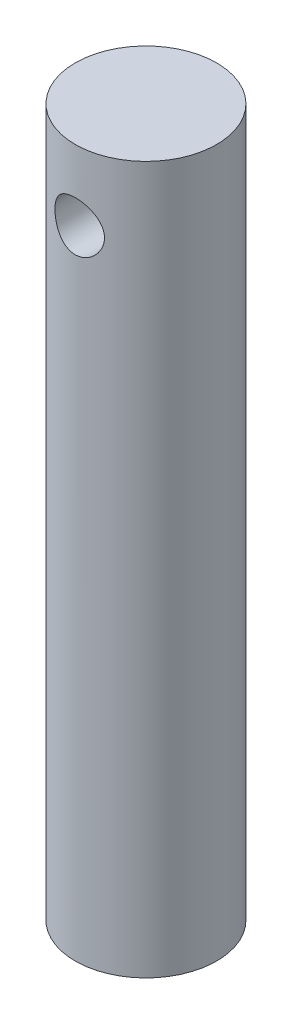
SolidWorks part; units mm, degrees
ref_plane "Plan de face" through (0, 0, 0) normal (0, 0, 1) x (1, 0, 0)
ref_plane "Plan de dessus" through (0, 0, 0) normal (0, 1, 0) x (1, 0, 0)
ref_plane "Plan de droite" through (0, 0, 0) normal (1, 0, 0) x (0, 0, -1)
sketch "Esquisse1" plane through (0, 0, 0) normal (0, 0, 1) x (1, 0, 0)
  line L1 (-10, 10) -> (10, 10)
  line L2 (-10, 10) -> (-10, -90)
  line L3 (-10, -90) -> (10, -90)
  line L4 (10, 10) -> (10, -90)
  circle A0 centre (0, 0) radius 3.5
  dimension "D3" = 7
  dimension "D4" = 10
  dimension "D5" = 10
  dimension "D1" = 20
  dimension "D2" = 100
extrude "Boss.-Extru.1" add sketch "Esquisse1" along normal blind 20
sketch "Esquisse3" plane through (0, 10, 0) normal (0, 1, 0) x (1, 0, 0)
  line L0 (0, 0) -> (0, -20) construction
  line L1 (10, -20) -> (-10, -20) construction
  line L2 (0, -20) -> (-10, -10) construction
  line L3 (-10, -20) -> (-10, 0) construction
  line L4 (-10, -10) -> (10, -10) construction
  line L5 (10, -20) -> (10, 0) construction
  line L6 (10, -10) -> (0, 0) construction
  line L7 (0, 0) -> (-10, -10) construction
  line L8 (-10, -10) -> (-10, 0)
  line L9 (-10, 0) -> (0, 0)
  line L10 (0, 0) -> (10, 0)
  line L11 (10, 0) -> (10, -10)
  line L12 (10, -10) -> (10, -20)
  line L13 (10, -20) -> (0, -20)
  line L14 (0, -20) -> (-10, -20)
  line L15 (-10, -20) -> (-10, -10)
  circle A0 centre (0, -10) radius 10
  line M1 (10, 0) -> (-10, 0)
  line M2 (-10, 0) -> (-10, -20)
  line M3 (-10, -20) -> (10, -20)
  line M4 (10, -20) -> (10, 0)
extrude "Enlèv. mat.-Extru.1" cut sketch "Esquisse3" against normal blind 100 contours A0 M1 M2 | A0 M4 M1 | A0 M3 M4 | A0 M2 M3
